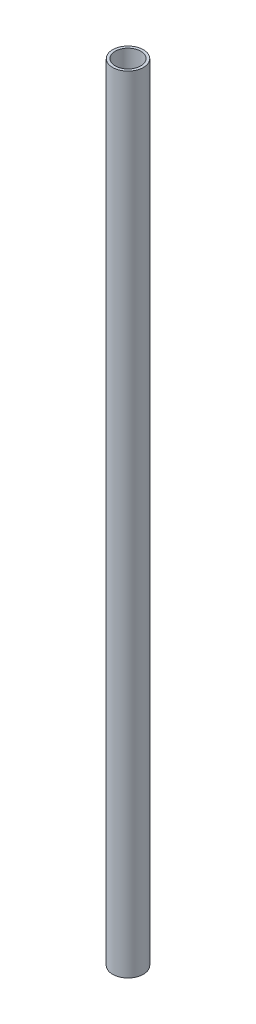
SolidWorks part; units mm, degrees
ref_plane "Front" through (0, 0, 0) normal (0, 0, 1) x (1, 0, 0)
ref_plane "Top" through (0, 0, 0) normal (0, 1, 0) x (1, 0, 0)
ref_plane "Right" through (0, 0, 0) normal (1, 0, 0) x (0, 0, -1)
sketch "Sketch1" plane through (0, 0, 0) normal (0, 1, 0) x (1, 0, 0)
  circle A0 centre (0, 0) radius 17.526
  circle A1 centre (0, 0) radius 21.082
  dimension "D1" = 42.164
  dimension "D2" = 35.052
extrude "Boss-Extrude1" add sketch "Sketch1" along normal blind 1075.69
